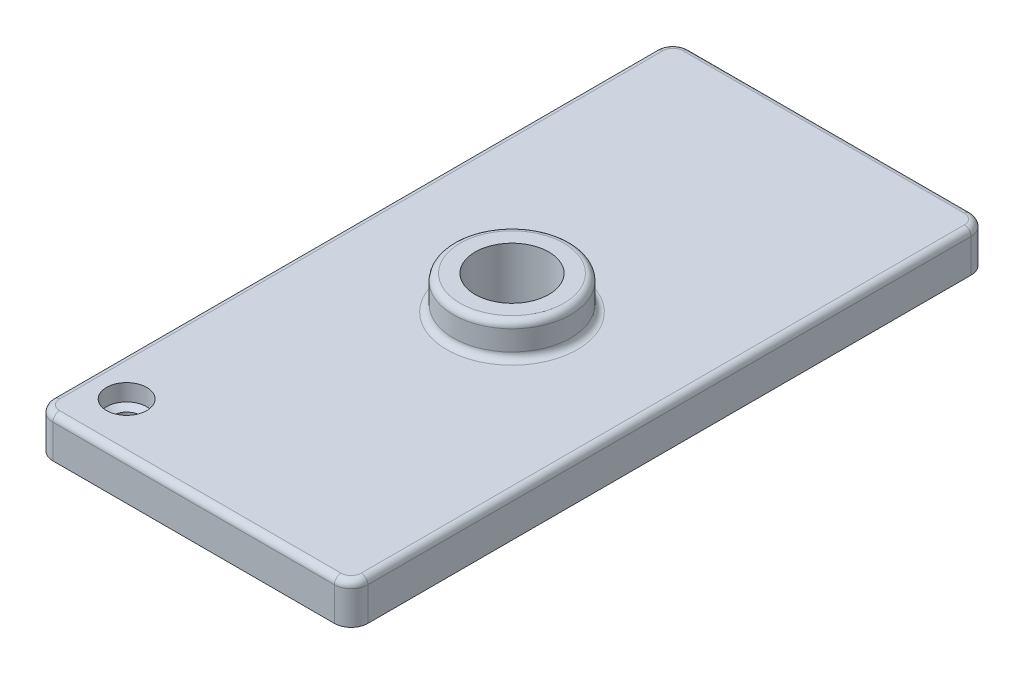
SolidWorks part; units mm, degrees
ref_plane "Front" through (0, 0, 0) normal (0, 0, 1) x (1, 0, 0)
ref_plane "Top" through (0, 0, 0) normal (0, 1, 0) x (1, 0, 0)
ref_plane "Right" through (0, 0, 0) normal (1, 0, 0) x (0, 0, -1)
sketch "Sketch1" plane through (0, 0, 0) normal (0, 1, 0) x (1, 0, 0)
  line L0 (-47, 95) -> (47, -95) construction
  line L1 (-47, -95) -> (47, -95)
  line L2 (-47, -95) -> (-47, 95)
  line L3 (-47, 95) -> (47, 95)
  line L4 (47, -95) -> (47, 95)
  dimension "D1" = 190
  dimension "D2" = 94
extrude "plate" add sketch "Sketch1" along normal blind 12
sketch "Sketch2" plane through (0, 12, 0) normal (0, 1, 0) x (-1, 0, 0)
  circle A0 centre (0, 0) radius 17.5
  dimension "D1" = 35
extrude "boss" add sketch "Sketch2" along normal blind 10
sketch "Sketch3" plane through (0, 22, 0) normal (0, 1, 0) x (-1, 0, 0)
  circle A0 centre (0, 0) radius 11
  dimension "D1" = 22
extrude "center hole" cut sketch "Sketch3" against normal through all
hole_wizard "pattern hole" positions "Sketch5" profile "Sketch4" legacy end condition through all
sketch "Sketch5" plane through (0, 12, 0) normal (0, 1, 0) x (-1, 0, 0)
  line L0 (47, 95) -> (-47, 95) construction
  line L1 (47, -95) -> (47, 95) construction
  point P0 (35, 80)
  dimension "D1" = 15
  dimension "D2" = 12
sketch "Sketch4" plane through (-35, 12, 80) normal (1, 0, 0) x (0, 0, 1)
  line L0 (0, 0) -> (0, 12)
  line L1 (0, 12) -> (4, 12)
  line L2 (4, 12) -> (4, 6.2017)
  line L3 (4, 6.2017) -> (6, 5)
  line L4 (6, 5) -> (6, 0)
  line L5 (6, 0) -> (0, 0)
  line L6 (0, -6.13) -> (0, 109.2824) construction
  line L7 (-4, 6.2017) -> (-6, 5) construction
  line L8 (0, 12) -> (-4, 12) construction
  dimension "Diameter" = 8
  dimension "Depth" = 12
  dimension "C-Drill Diameter" = 12
  dimension "C-Drill Depth" = 5
  dimension "C-Drill Angle" = 118
fillet "R5" radius 5 4 edges at (-47, 6, -95) (47, 6, -95) (47, 6, 95) (-47, 6, 95)
fillet "R2" radius 2 10 edges at (0, 12, -17.5) (0, 22, 17.5) (47, 12, 0) (0, 12, 95) (-47, 12, 0) (0, 12, -95) (45.5355, 12, -93.5355) (-45.5355, 12, -93.5355) (-45.5355, 12, 93.5355) (45.5355, 12, 93.5355)
